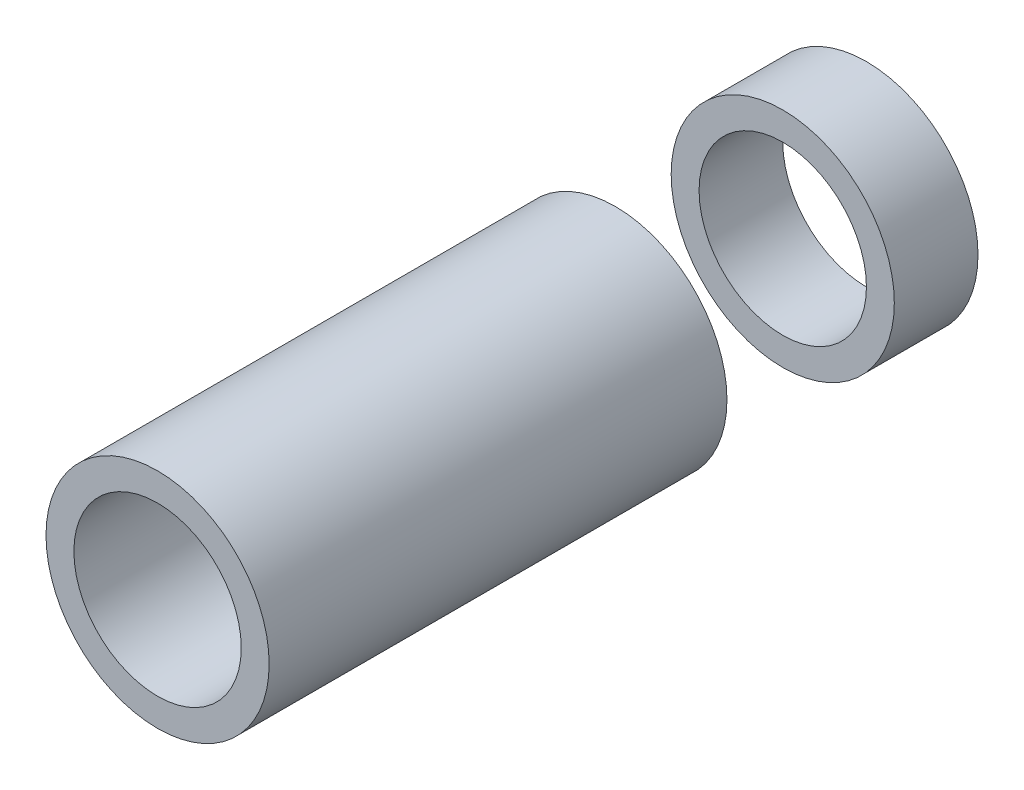
SolidWorks part; units mm, degrees
material "PA Type 6"
ref_plane "Front Plane" through (0, 0, 0) normal (0, 0, 1) x (1, 0, 0)
ref_plane "Top Plane" through (0, 0, 0) normal (0, 1, 0) x (1, 0, 0)
ref_plane "Right Plane" through (0, 0, 0) normal (1, 0, 0) x (0, 0, -1)
sketch "Sketch2" plane through (0, 0, 0) normal (1, 0, 0) x (0, 0, -1)
  line L0 (0, 6) -> (32.8261, 6)
  line L1 (32.8261, 6) -> (44.8261, 6) construction
  line L2 (44.8261, 6) -> (50.8261, 6)
  line L3 (0, 6) -> (0, 8)
  line L4 (26.3478, 0) -> (0, 0) construction
  line L5 (0, 8) -> (32.8261, 8)
  line L6 (32.8261, 8) -> (32.8261, 6)
  line L7 (44.8261, 6) -> (44.8261, 8)
  line L8 (44.8261, 8) -> (50.8261, 8)
  line L9 (50.8261, 8) -> (50.8261, 6)
  dimension "D1" = 12
  dimension "D2" = 16
  dimension "D3" = 12
  dimension "D4" = 6
  dimension "D5" = 32.8261
revolve "Revolve1" add sketch "Sketch2" angle 360 about L4
